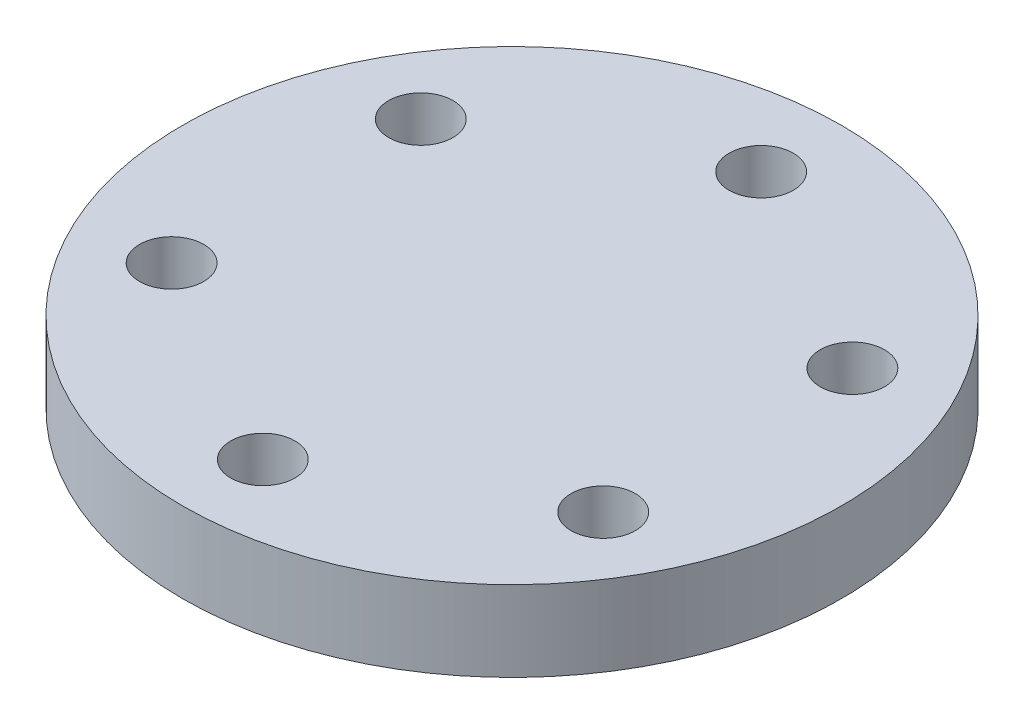
SolidWorks part; units mm, degrees
ref_plane "前基準面" through (0, 0, 0) normal (0, 0, 1) x (1, 0, 0)
ref_plane "上基準面" through (0, 0, 0) normal (0, 1, 0) x (1, 0, 0)
ref_plane "右基準面" through (0, 0, 0) normal (1, 0, 0) x (0, 0, -1)
sketch "草圖1" plane through (0, 0, 0) normal (0, 1, 0) x (1, 0, 0)
  circle A0 centre (0, 0) radius 20.5
  dimension "D1" = 41
extrude "填料-伸長1" add sketch "草圖1" along normal blind 5
sketch "草圖2" plane through (0, 5, 0) normal (0, 1, 0) x (1, 0, 0)
  circle A0 centre (0, 15.5) radius 2
  dimension "D1" = 4
  dimension "D2" = 15.5
extrude "除料-伸長1" cut sketch "草圖2" against normal up to next
pattern_circular "環狀複製排列1" count 6 over 360 about axis through (0, 0, 0) along (0, 1, 0) of "除料-伸長1"
